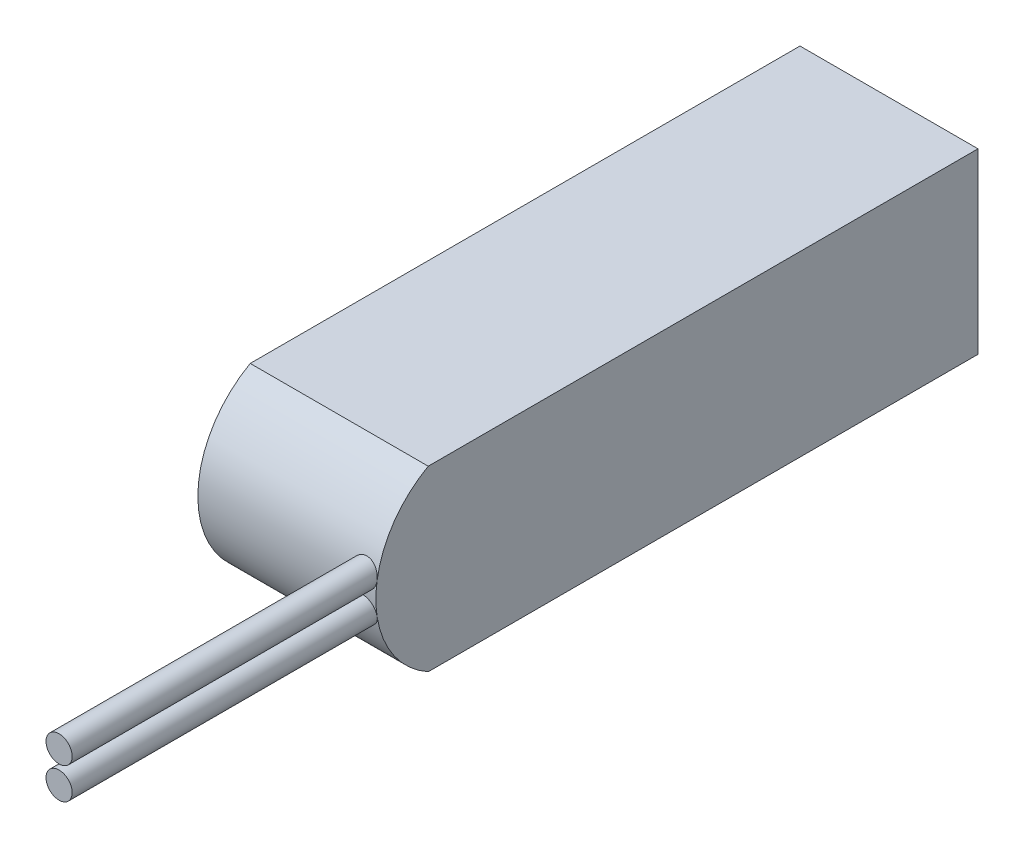
SolidWorks part; units mm, degrees
ref_plane "Plan de face" through (0, 0, 0) normal (0, 0, 1) x (1, 0, 0)
ref_plane "Plan de dessus" through (0, 0, 0) normal (0, 1, 0) x (1, 0, 0)
ref_plane "Plan de droite" through (0, 0, 0) normal (1, 0, 0) x (0, 0, -1)
sketch "Esquisse1" plane through (0, 0, 0) normal (0, 0, 1) x (1, 0, 0)
  line L1 (0, 0) -> (34, 0)
  line L2 (0, 0) -> (0, 34)
  line L3 (0, 34) -> (34, 34)
  line L4 (34, 0) -> (34, 34)
  dimension "D1" = 34
  dimension "D2" = 34
extrude "Boss.-Extru.1" add sketch "Esquisse1" along normal blind 105
sketch "Esquisse2" plane through (34, 0, 0) normal (1, 0, 0) x (0, 0, -1)
  line L0 (-105, 0) -> (-105, 34) construction
  line L1 (-105, 34) -> (-105, 0)
  arc A0 (-105, 34) -> (-105, 0) centre (-95.55, 17) ccw
  point P7 (-115, 17)
  dimension "D1" = 10
extrude "Boss.-Extru.2" add sketch "Esquisse2" against normal up to vertex (34 mm away) up to point (0, 34, 105)
sketch "Esquisse3" plane through (0, 0, 0) normal (0, 0, -1) x (-1, 0, 0)
  line L0 (-34, 0) -> (-34, 34) construction
  line L1 (-31.5, 20) -> (-31.5, 14) construction
  line L2 (-34, 17) -> (0, 17) construction
  line L3 (0, 34) -> (0, 0) construction
  circle A0 centre (-31.5, 20) radius 2.5
  circle A1 centre (-31.5, 14) radius 2.5
  point P9 (-31.5, 14)
  dimension "D1" = 5
  dimension "D2" = 3
  dimension "D3" = 3
extrude "Boss.-Extru.3" add sketch "Esquisse3" against normal blind 173
